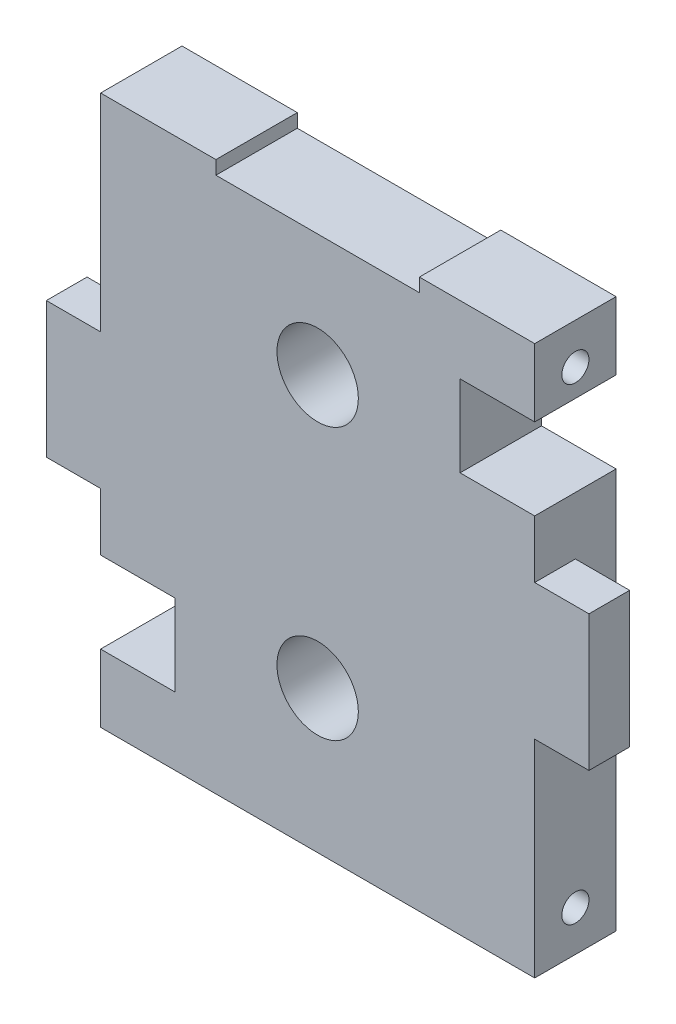
SolidWorks part; units mm, degrees
ref_plane "前视基准面" through (0, 0, 0) normal (0, 0, 1) x (1, 0, 0)
ref_plane "上视基准面" through (0, 0, 0) normal (0, 1, 0) x (1, 0, 0)
ref_plane "右视基准面" through (0, 0, 0) normal (1, 0, 0) x (0, 0, -1)
other "Configuration Table"
sketch "草图1" plane through (0, 0, 0) normal (0, 0, 1) x (1, 0, 0)
  line L0 (0, 0) -> (0, -15.25)
  line L1 (0, -15.25) -> (-4, -15.25)
  line L2 (-4, -15.25) -> (-4, -25.25)
  line L3 (-4, -25.25) -> (0, -25.25)
  line L4 (0, -25.25) -> (0, -29.5)
  line L5 (0, -29.5) -> (5.5, -29.5)
  line L6 (5.5, -29.5) -> (5.5, -35.5)
  line L7 (5.5, -35.5) -> (0, -35.5)
  line L8 (0, -35.5) -> (0, -40.5)
  line L9 (0, -40.5) -> (32, -40.5)
  line L11 (32, 0) -> (0, 0)
  line L12 (32, 0) -> (32, -5)
  line L13 (32, -5) -> (26.5, -5)
  line L14 (26.5, -5) -> (26.5, -11)
  line L15 (26.5, -11) -> (32, -11)
  line L16 (32, -11) -> (32, -15.25)
  line L17 (32, -15.25) -> (36, -15.25)
  line L18 (36, -15.25) -> (36, -25.25)
  line L19 (36, -25.25) -> (32, -25.25)
  line L20 (32, -25.25) -> (32, -40.5)
  line L21 (16, 0) -> (16, -40.5) construction
  circle A0 centre (16, -10) radius 3
  circle A1 centre (16, -30) radius 3
  point P13 (-2, -15.25)
  dimension "D9" = 6
  dimension "D10" = 6
  dimension "D1" = 4
  dimension "D2" = 5.5
  dimension "D3" = 15.25
  dimension "D4" = 10
  dimension "D5" = 40.5
  dimension "D6" = 5
  dimension "D7" = 6
  dimension "D8" = 32
  dimension "D11" = 10
  dimension "D12" = 30
extrude "凸台-拉伸1" add sketch "草图1" along normal blind 3
sketch "草图2" plane through (0, 0, 3) normal (0, 0, 1) x (1, 0, 0)
  line L0 (0, 0) -> (0, -29.5)
  line L1 (0, -29.5) -> (5.5, -29.5)
  line L2 (5.5, -29.5) -> (5.5, -35.5)
  line L3 (5.5, -35.5) -> (0, -35.5)
  line L4 (0, -35.5) -> (0, -40.5)
  line L5 (0, -40.5) -> (32, -40.5)
  line L6 (32, -40.5) -> (32, -11)
  line L7 (32, -11) -> (26.5, -11)
  line L8 (26.5, -11) -> (26.5, -5)
  line L9 (26.5, -5) -> (32, -5)
  line L10 (32, -5) -> (32, 0)
  line L11 (32, 0) -> (0, 0)
  circle A0 centre (16, -10) radius 3
  circle A1 centre (16, -30) radius 3
extrude "凸台-拉伸2" add sketch "草图2" against normal blind 6
sketch "草图3" plane through (32, 0, 0) normal (1, 0, 0) x (0, 0, -1)
  line L0 (0, 0) -> (0, -50000) construction
  line L1 (-3, -40.5) -> (3, -40.5) construction
  line L2 (-3, 0) -> (3, 0) construction
  circle A0 centre (0, -3) radius 1
  circle A1 centre (0, -37.5) radius 1
  dimension "D1" = 2
  dimension "D2" = 2
  dimension "D3" = 3
  dimension "D4" = 3
extrude "切除-拉伸1" cut sketch "草图3" against normal through all
sketch "草图6" plane through (0, 0, 3) normal (0, 0, 1) x (1, 0, 0)
  line L7 (16, -30) -> (16, -10) construction
  line L8 (32, 0) -> (0, 0) construction
  line L9 (8.5, -1) -> (23.5, -1)
  line L10 (8.5, -1) -> (8.5, 0)
  line L11 (8.5, 0) -> (23.5, 0)
  line L12 (23.5, -1) -> (23.5, 0)
  line L13 (8.5, -1) -> (23.5, 0) construction
  line L14 (8.5, 0) -> (23.5, -1) construction
  point P11 (16, -0.5)
  dimension "D3" = 15
  dimension "D4" = 1
extrude "切除-拉伸5" cut sketch "草图6" against normal blind 10
